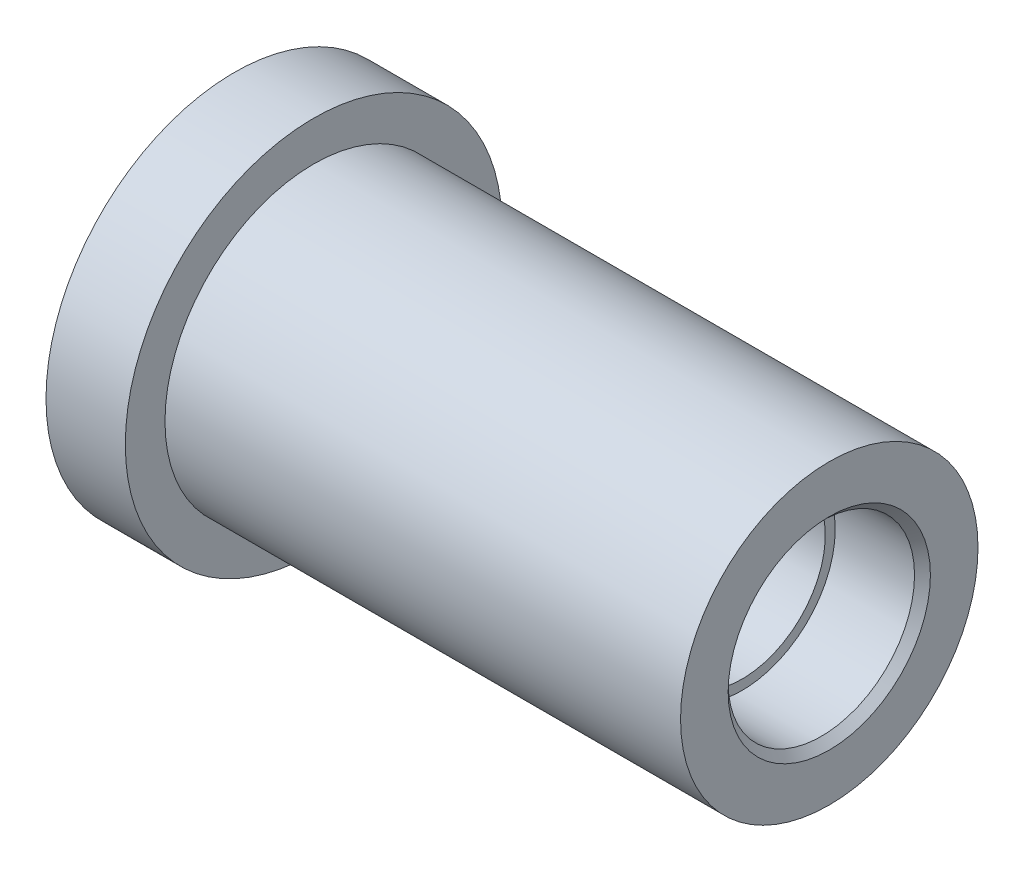
SolidWorks part; units mm, degrees
material "3.3523 (EN-AW 5052)"
ref_plane "Спереди" through (0, 0, 0) normal (0, 0, 1) x (1, 0, 0)
ref_plane "Сверху" through (0, 0, 0) normal (0, 1, 0) x (1, 0, 0)
ref_plane "Справа" through (0, 0, 0) normal (1, 0, 0) x (0, 0, -1)
sketch "Эскиз1" plane through (0, 0, 0) normal (0, 0, 1) x (1, 0, 0)
  line L0 (0, 0) -> (91, 0) construction
  line L5 (-75, 23.5) -> (-75, 47.5)
  line L6 (-75, 47.5) -> (75, 47.5)
  line L7 (75, 47.5) -> (75, 23.5)
  line L8 (75, 23.5) -> (53, 23.5)
  line L9 (53, 23.5) -> (53, 21)
  line L10 (53, 21) -> (-53, 21)
  line L14 (0, 47.5) -> (0, -49952.5) construction
  line L17 (-53, 23.5) -> (-53, 21)
  line L18 (-75, 23.5) -> (-53, 23.5)
  point P4 (-53, 21)
  point P6 (-75, 23.5)
  point P9 (-75, 47.5)
  point P10 (75, 47.5)
  point P11 (75, 23.5)
  point P13 (53, 21)
  point P17 (0, 47.5)
  dimension "D2" = 22
  dimension "D8" = 47
  dimension "D9" = 150
  dimension "D10" = 95
  dimension "D11" = 42
revolve "Повернуть1" add sketch "Эскиз1" angle 360 about L0
sketch "Эскиз4" plane through (-75, 0, 0) normal (1, 0, 0) x (0, 0, -1)
  circle A0 centre (0, 0) radius 37.5 construction
  point P0 (0, 37.5)
  dimension "D1" = 75
hole_wizard "Отверстие обработанное метчиком M61" positions "Эскиз4" profile "Эскиз3" tap size "M6" standard "ISO"
sketch "Эскиз3" plane through (-75, 37.5, 0) normal (0, 1, 0) x (0, 0, 1)
  line L0 (0, 0) -> (0, 17)
  line L1 (0, 17) -> (2.5, 15.4978)
  line L2 (2.5, 15.4978) -> (2.5, 0)
  line L5 (2.5, 0) -> (0, 0)
  line L10 (0, 17) -> (-2.5, 15.4978) construction
  line L11 (0, -6.35) -> (0, 107.95) construction
  dimension "Диаметр сверла" = 5
  dimension "Глубина сверла" = 17
  dimension "Угол заточки сверла" = 118
cosmetic thread "Отверстие резьбы1" parameters "D1"=12, "D2"=6
pattern_circular "Круговой массив1" count 6 over 360 about axis through (0, 0, 0) along (1, 0, 0) of "Отверстие обработанное метчиком M61"
cosmetic thread "Отверстие резьбы2" parameters "D1"=12, "D2"=6
cosmetic thread "Отверстие резьбы3" parameters "D1"=12, "D2"=6
cosmetic thread "Отверстие резьбы4" parameters "D1"=12, "D2"=6
cosmetic thread "Отверстие резьбы5" parameters "D1"=12, "D2"=6
cosmetic thread "Отверстие резьбы6" parameters "D1"=12, "D2"=6
chamfer "Фаска2" distance 1 angle 45 6 edges at (-75, 18.75, -29.976) (-75, -18.75, -29.976) (-75, -37.5, 2.5) (-75, -18.75, 34.976) (-75, 18.75, 34.976) (-75, 37.5, 2.5)
chamfer "Фаска1" distance 2 angle 45 1 edges at (75, 0, 23.5)
sketch "Эскиз5" plane through (0, 0, 0) normal (0, 0, 1) x (1, 0, 0)
  line L0 (-75, 0) -> (75, 0) construction
  line L1 (-75, 47.5) -> (-75, -47.5) construction
  line L2 (75, 0) -> (-75, 0) construction
  line L3 (75, 0) -> (73, 0) construction
  line L4 (-55, 47.5) -> (-55, 37.5)
  line L5 (-75, 47.5) -> (75, 47.5) construction
  line L6 (-75, 47.5) -> (-75, 0) construction
  line L7 (-75, 0) -> (75, 0) construction
  line L8 (75, 47.5) -> (75, 0) construction
  line L9 (-55, 37.5) -> (75, 37.5)
  line L10 (75, 47.5) -> (75, 37.5)
  line L11 (75, -47.5) -> (75, 47.5) construction
  line L13 (-55, 47.5) -> (75, 47.5)
  dimension "D1" = 20
  dimension "D2" = 0
revolve "Вырез-Повернуть1" cut sketch "Эскиз5" angle 360 about L0
sketch "Эскиз6" plane through (-75, 0, 0) normal (-1, 0, 0) x (0, 0, 1)
  circle A0 centre (0, 0) radius 23.5 construction
  circle A1 centre (0, 0) radius 23.5
  circle A2 centre (0, 0) radius 27.5
  dimension "D1" = 55
extrude "Вырез-Вытянуть1" cut sketch "Эскиз6" against normal blind 5
chamfer "Фаска3" distance 1 angle 45 2 edges at (-70, 0, 23.5) (-75, 0, 27.5)
